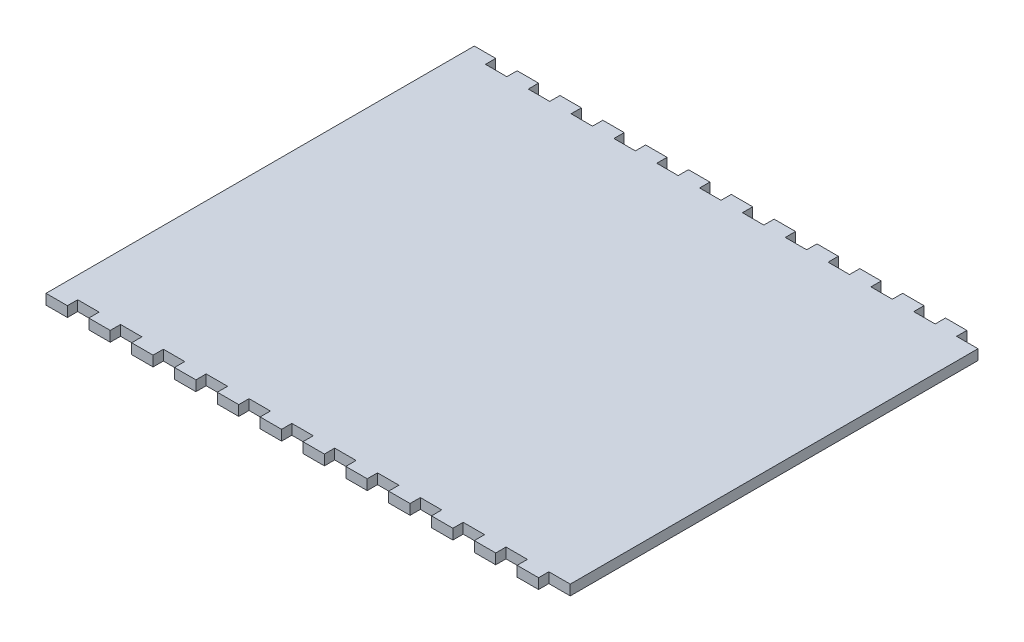
SolidWorks part; units mm, degrees
ref_plane "Front Plane" through (0, 0, 0) normal (0, 0, 1) x (1, 0, 0)
ref_plane "Top Plane" through (0, 0, 0) normal (0, 1, 0) x (1, 0, 0)
ref_plane "Right Plane" through (0, 0, 0) normal (1, 0, 0) x (0, 0, -1)
sketch "Sketch1" plane through (0, 0, 0) normal (0, 1, 0) x (1, 0, 0)
  line L1 (76.2, -63.5) -> (-76.2, -63.5)
  line L2 (76.2, -63.5) -> (76.2, 63.5)
  line L3 (76.2, 63.5) -> (-76.2, 63.5)
  line L4 (-76.2, -63.5) -> (-76.2, 63.5)
  line L5 (76.2, -63.5) -> (-76.2, 63.5) construction
  line L6 (76.2, 63.5) -> (-76.2, -63.5) construction
  point P0 (0, 0)
  dimension "D1" = 127
  dimension "D2" = 152.4
extrude "Boss-Extrude1" add sketch "Sketch1" along normal blind 3.048
sketch "Sketch2" plane through (0, 3.048, 0) normal (0, 1, 0) x (1, 0, 0)
  line L0 (-76.2, -63.5) -> (-69.85, -63.5)
  line L1 (-76.2, -63.5) -> (76.2, -63.5) construction
  line L2 (-69.85, -63.5) -> (-69.85, -60.452)
  line L3 (-69.85, -60.452) -> (-63.5, -60.452)
  line L4 (-63.5, -60.452) -> (-63.5, -63.5)
  line L5 (-63.5, -63.5) -> (-57.15, -63.5)
  line L6 (-57.15, -63.5) -> (-57.15, -60.452)
  line L7 (-57.15, -60.452) -> (-50.8, -60.452)
  line L8 (-50.8, -60.452) -> (-50.8, -63.5)
  line L9 (-50.8, -63.5) -> (-44.45, -63.5)
  line L10 (-44.45, -63.5) -> (-44.45, -60.452)
  line L11 (-44.45, -60.452) -> (-38.1, -60.452)
  line L12 (-38.1, -60.452) -> (-38.1, -63.5)
  line L13 (-38.1, -63.5) -> (-31.75, -63.5)
  line L14 (-31.75, -63.5) -> (-31.75, -60.452)
  line L15 (-31.75, -60.452) -> (-25.4, -60.452)
  line L16 (-25.4, -60.452) -> (-25.4, -63.5)
  line L17 (-25.4, -63.5) -> (-19.05, -63.5)
  line L18 (-19.05, -63.5) -> (-19.05, -60.452)
  line L19 (-19.05, -60.452) -> (-12.7, -60.452)
  line L20 (-12.7, -60.452) -> (-12.7, -63.5)
  line L21 (-12.7, -63.5) -> (-6.35, -63.5)
  line L22 (-6.35, -63.5) -> (-6.35, -60.452)
  line L23 (-6.35, -60.452) -> (0, -60.452)
  line L24 (0, -60.452) -> (0, -63.5)
  line L25 (0, -63.5) -> (6.35, -63.5)
  line L26 (6.35, -63.5) -> (6.35, -60.452)
  line L27 (6.35, -60.452) -> (12.7, -60.452)
  line L28 (12.7, -60.452) -> (12.7, -63.5)
  line L29 (12.7, -63.5) -> (19.05, -63.5)
  line L30 (19.05, -63.5) -> (19.05, -60.452)
  line L31 (19.05, -60.452) -> (25.4, -60.452)
  line L32 (25.4, -60.452) -> (25.4, -63.5)
  line L33 (25.4, -63.5) -> (31.75, -63.5)
  line L34 (31.75, -63.5) -> (31.75, -60.452)
  line L35 (31.75, -60.452) -> (38.1, -60.452)
  line L36 (38.1, -60.452) -> (38.1, -63.5)
  line L37 (38.1, -63.5) -> (44.45, -63.5)
  line L38 (44.45, -63.5) -> (44.45, -60.452)
  line L39 (44.45, -60.452) -> (50.8, -60.452)
  line L40 (50.8, -60.452) -> (50.8, -63.5)
  line L41 (50.8, -63.5) -> (57.15, -63.5)
  line L42 (57.15, -63.5) -> (57.15, -60.452)
  line L43 (57.15, -60.452) -> (63.5, -60.452)
  line L44 (63.5, -60.452) -> (63.5, -63.5)
  line L45 (63.5, -63.5) -> (69.85, -63.5)
  line L46 (69.85, -63.5) -> (69.85, -60.452)
  line L47 (69.85, -60.452) -> (76.2, -60.452)
  line L48 (76.2, -60.452) -> (76.2, -63.5)
  line L49 (-76.2, -63.5) -> (76.2, -63.5)
  line L50 (76.2, 0) -> (-76.2, 0)
  line L51 (76.2, -63.5) -> (76.2, 63.5) construction
  line L52 (-76.2, 63.5) -> (-76.2, -63.5) construction
  line L53 (-76.2, 63.5) -> (76.2, 63.5)
  line L54 (76.2, 60.452) -> (76.2, 63.5)
  line L55 (69.85, 60.452) -> (76.2, 60.452)
  line L56 (69.85, 63.5) -> (69.85, 60.452)
  line L57 (63.5, 63.5) -> (69.85, 63.5)
  line L58 (63.5, 60.452) -> (63.5, 63.5)
  line L59 (57.15, 60.452) -> (63.5, 60.452)
  line L60 (57.15, 63.5) -> (57.15, 60.452)
  line L61 (50.8, 63.5) -> (57.15, 63.5)
  line L62 (50.8, 60.452) -> (50.8, 63.5)
  line L63 (44.45, 60.452) -> (50.8, 60.452)
  line L64 (44.45, 63.5) -> (44.45, 60.452)
  line L65 (38.1, 63.5) -> (44.45, 63.5)
  line L66 (38.1, 60.452) -> (38.1, 63.5)
  line L67 (31.75, 60.452) -> (38.1, 60.452)
  line L68 (31.75, 63.5) -> (31.75, 60.452)
  line L69 (25.4, 63.5) -> (31.75, 63.5)
  line L70 (25.4, 60.452) -> (25.4, 63.5)
  line L71 (19.05, 60.452) -> (25.4, 60.452)
  line L72 (19.05, 63.5) -> (19.05, 60.452)
  line L73 (12.7, 63.5) -> (19.05, 63.5)
  line L74 (12.7, 60.452) -> (12.7, 63.5)
  line L75 (6.35, 60.452) -> (12.7, 60.452)
  line L76 (6.35, 63.5) -> (6.35, 60.452)
  line L77 (0, 63.5) -> (6.35, 63.5)
  line L78 (0, 60.452) -> (0, 63.5)
  line L79 (-6.35, 60.452) -> (0, 60.452)
  line L80 (-6.35, 63.5) -> (-6.35, 60.452)
  line L81 (-12.7, 63.5) -> (-6.35, 63.5)
  line L82 (-12.7, 60.452) -> (-12.7, 63.5)
  line L83 (-19.05, 60.452) -> (-12.7, 60.452)
  line L84 (-19.05, 63.5) -> (-19.05, 60.452)
  line L85 (-25.4, 63.5) -> (-19.05, 63.5)
  line L86 (-25.4, 60.452) -> (-25.4, 63.5)
  line L87 (-31.75, 60.452) -> (-25.4, 60.452)
  line L88 (-31.75, 63.5) -> (-31.75, 60.452)
  line L89 (-38.1, 63.5) -> (-31.75, 63.5)
  line L90 (-38.1, 60.452) -> (-38.1, 63.5)
  line L91 (-44.45, 60.452) -> (-38.1, 60.452)
  line L92 (-44.45, 63.5) -> (-44.45, 60.452)
  line L93 (-50.8, 63.5) -> (-44.45, 63.5)
  line L94 (-50.8, 60.452) -> (-50.8, 63.5)
  line L95 (-57.15, 60.452) -> (-50.8, 60.452)
  line L96 (-57.15, 63.5) -> (-57.15, 60.452)
  line L97 (-63.5, 63.5) -> (-57.15, 63.5)
  line L98 (-63.5, 60.452) -> (-63.5, 63.5)
  line L99 (-69.85, 60.452) -> (-63.5, 60.452)
  line L100 (-69.85, 63.5) -> (-69.85, 60.452)
  line L101 (-76.2, 63.5) -> (-69.85, 63.5)
  line M6 (-76.2, -63.5) -> (76.2, -63.5)
  line M7 (76.2, -63.5) -> (76.2, 63.5)
  line M8 (76.2, 63.5) -> (-76.2, 63.5)
  dimension "D1" = 6.35
  dimension "D2" = 6.35
  dimension "D3" = 3.048
  dimension "D4" = 12
extrude "Cut-Extrude1" cut sketch "Sketch2" against normal through all contours L4 L3 L2 M6 | L8 L7 L6 M6 | L12 L11 L10 M6 | L16 L15 L14 M6 | L20 L19 L18 M6 | L24 L23 L22 M6 | L28 L27 L26 M6 | L32 L31 L30 M6 | L40 L39 L38 M6 | L44 L43 L42 M6 | L36 L35 L34 M6 | L47 L46 M6 M7 | L100 L99 L98 M8 | L96 L95 L94 M8 | L92 L91 L90 M8 | L88 L87 L86 M8 | L84 L83 L82 M8 | L80 L79 L78 M8 | L76 L75 L74 M8 | L72 L71 L70 M8 | L68 L67 L66 M8 | L64 L63 L62 M8 | L60 L59 L58 M8 | L56 L55 M8 M7
